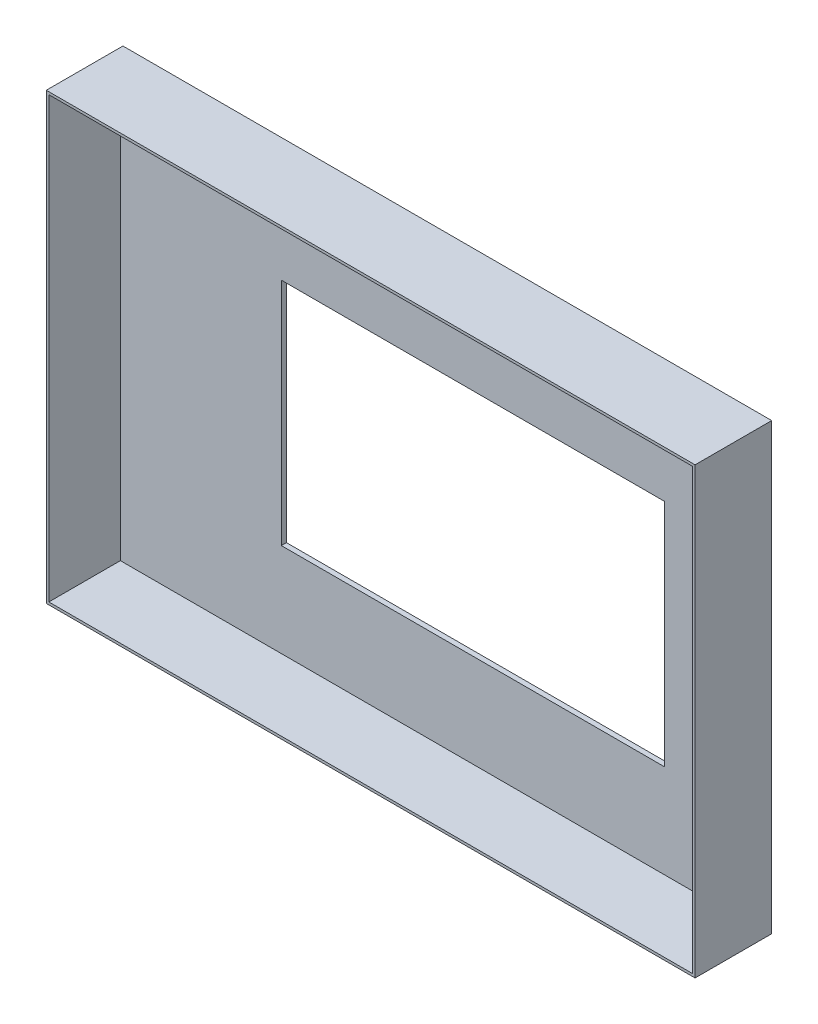
SolidWorks part; units mm, degrees
ref_plane "Front Plane" through (0, 0, 0) normal (0, 0, 1) x (1, 0, 0)
ref_plane "Top Plane" through (0, 0, 0) normal (0, 1, 0) x (1, 0, 0)
ref_plane "Right Plane" through (0, 0, 0) normal (1, 0, 0) x (0, 0, -1)
sketch "Sketch1" plane through (0, 0, 0) normal (0, 0, 1) x (1, 0, 0)
  line L1 (-61.595, 27.305) -> (65.405, 27.305)
  line L2 (-61.595, 27.305) -> (-61.595, -59.695)
  line L3 (-61.595, -59.695) -> (65.405, -59.695)
  line L4 (65.405, 27.305) -> (65.405, -59.695)
  dimension "D1" = 127
  dimension "D2" = 87
extrude "Boss-Extrude1" add sketch "Sketch1" along normal blind 15
sketch "Sketch2" plane through (0, 0, 15) normal (0, 0, 1) x (1, 0, 0)
  line L0 (-61.595, 27.305) -> (-61.595, -59.695) construction
  line L1 (-61.095, 26.805) -> (64.905, 26.805)
  line L2 (-61.095, 26.805) -> (-61.095, -59.195)
  line L3 (-61.095, -59.195) -> (64.905, -59.195)
  line L4 (64.905, 26.805) -> (64.905, -59.195)
  line L5 (65.405, 27.305) -> (-61.595, 27.305) construction
  dimension "D1" = 126
  dimension "D2" = 86
  dimension "D3" = 0.5
  dimension "D4" = 0.5
extrude "Cut-Extrude1" cut sketch "Sketch2" against normal blind 14
sketch "Sketch3" plane through (0, 0, 0) normal (0, 0, -1) x (-1, 0, 0)
  line L0 (-65.405, -59.695) -> (-65.405, 27.305) construction
  line L1 (-45.405, 4.1165) -> (29.595, 4.1165)
  line L2 (-45.405, 4.1165) -> (-45.405, -40.8835)
  line L3 (-45.405, -40.8835) -> (29.595, -40.8835)
  line L4 (29.595, 4.1165) -> (29.595, -40.8835)
  dimension "D1" = 45
  dimension "D2" = 75
  dimension "D3" = 20
extrude "Cut-Extrude2" cut sketch "Sketch3" against normal blind 1
sketch "Sketch9" plane through (0, 0, 0) normal (0, 0, -1) x (-1, 0, 0)
  text T0 "<b><i>SKITWALL </i></b>                    " font "Century Gothic" height 3.175
  text T1 "<b><i>SKILLSTICK                    </i></b>" font "Century Gothic" height 3.175
